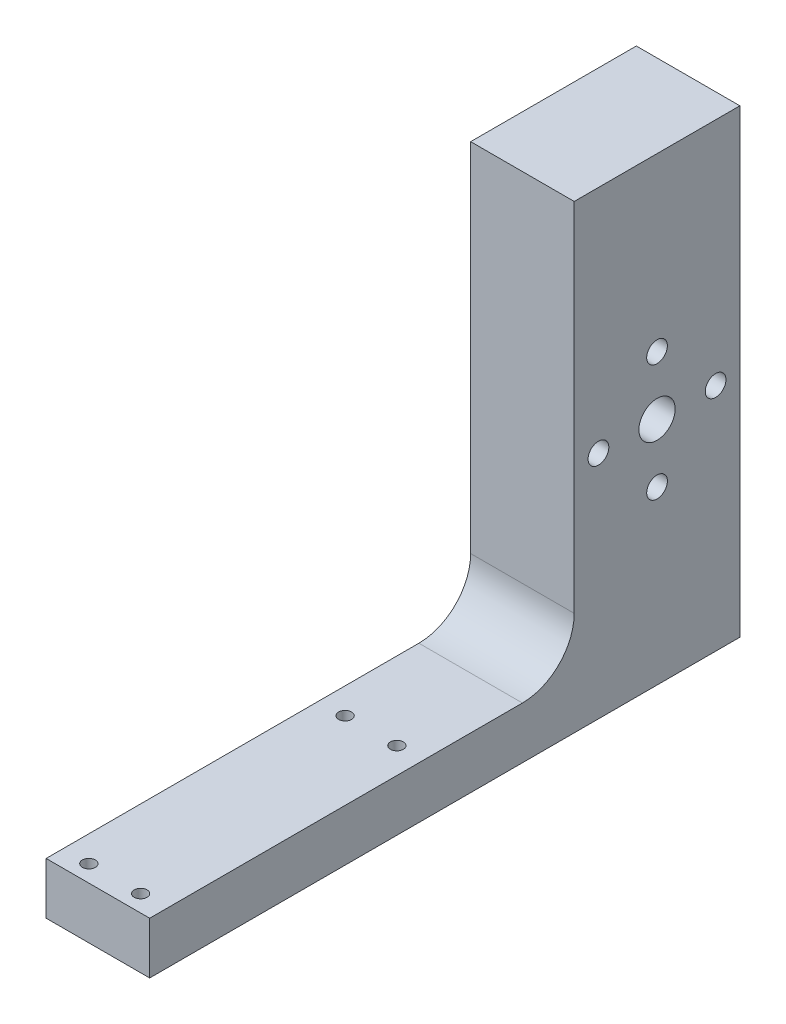
SolidWorks part; units mm, degrees
ref_plane "Front" through (0, 0, 0) normal (0, 0, 1) x (1, 0, 0)
ref_plane "Top" through (0, 0, 0) normal (0, 1, 0) x (1, 0, 0)
ref_plane "Right" through (0, 0, 0) normal (1, 0, 0) x (0, 0, -1)
sketch "Sketch1" plane through (0, 0, 0) normal (0, 1, 0) x (1, 0, 0)
  line L0 (0, 44) -> (20, 44)
  line L1 (0, 0) -> (20, 0)
  line L2 (0, 0) -> (0, 44)
  line L3 (0, 44) -> (20, 44)
  line L4 (20, 0) -> (20, 44)
  line L5 (0, 44) -> (0, 76)
  line L6 (20, 44) -> (20, 76)
  line L7 (0, 76) -> (20, 76)
  line L8 (20, 0) -> (0, 0)
  line L9 (20, 0) -> (20, -6)
  line L10 (0, 0) -> (0, -6)
  line L11 (20, -6) -> (0, -6)
  line L12 (0, 22) -> (20, 22)
  line L13 (10, -2.75) -> (10, 46.75)
  line L14 (5, -2.75) -> (15, -2.75)
  line L15 (5, 46.75) -> (15, 46.75)
  circle A0 centre (5, -2.75) radius 1.25
  circle A1 centre (15, -2.75) radius 1.25
  circle A2 centre (5, 46.75) radius 1.25
  circle A3 centre (15, 46.75) radius 1.25
  point P14 (10, 22)
  point P17 (10, -2.75)
  point P20 (10, 46.75)
  dimension "D1" = 44
  dimension "D2" = 20
  dimension "D3" = 6
  dimension "D4" = 32
  dimension "D5" = 49.5
extrude "Boss-Extrude1" add sketch "Sketch1" along normal blind 10
sketch "Sketch2" plane through (0, 0, -76) normal (0, 0, -1) x (-1, 0, 0)
  line L0 (-20, 0) -> (0, 0)
  line L1 (-20, 0) -> (-20, 88.9)
  line L2 (0, 0) -> (0, 88.9)
  line L3 (-20, 88.9) -> (0, 88.9)
  dimension "D1" = 88.9
extrude "Boss-Extrude2" add sketch "Sketch2" along normal blind 32
fillet "Fillet1" radius 10 1 edges at (10, 10, -76)
sketch "Sketch3" plane through (20, 0, 0) normal (1, 0, 0) x (0, 0, -1)
  line L0 (92, 88.9) -> (92, 0)
  line L1 (108, 88.9) -> (76, 88.9) construction
  line L2 (-6, 0) -> (108, 0) construction
  circle A0 centre (92, 44.45) radius 11.3137
  circle A1 centre (92, 33.1363) radius 2
  circle A2 centre (103.3137, 44.45) radius 2
  circle A3 centre (80.6863, 44.45) radius 2
  circle A4 centre (92, 55.7637) radius 2
  circle A5 centre (92, 44.45) radius 3.5
extrude "Cut-Extrude1" cut sketch "Sketch3" against normal blind 32 contours L0 A5 | L0 A5 | A0 A2 | A0 A2 | A1 | A3 | A4
